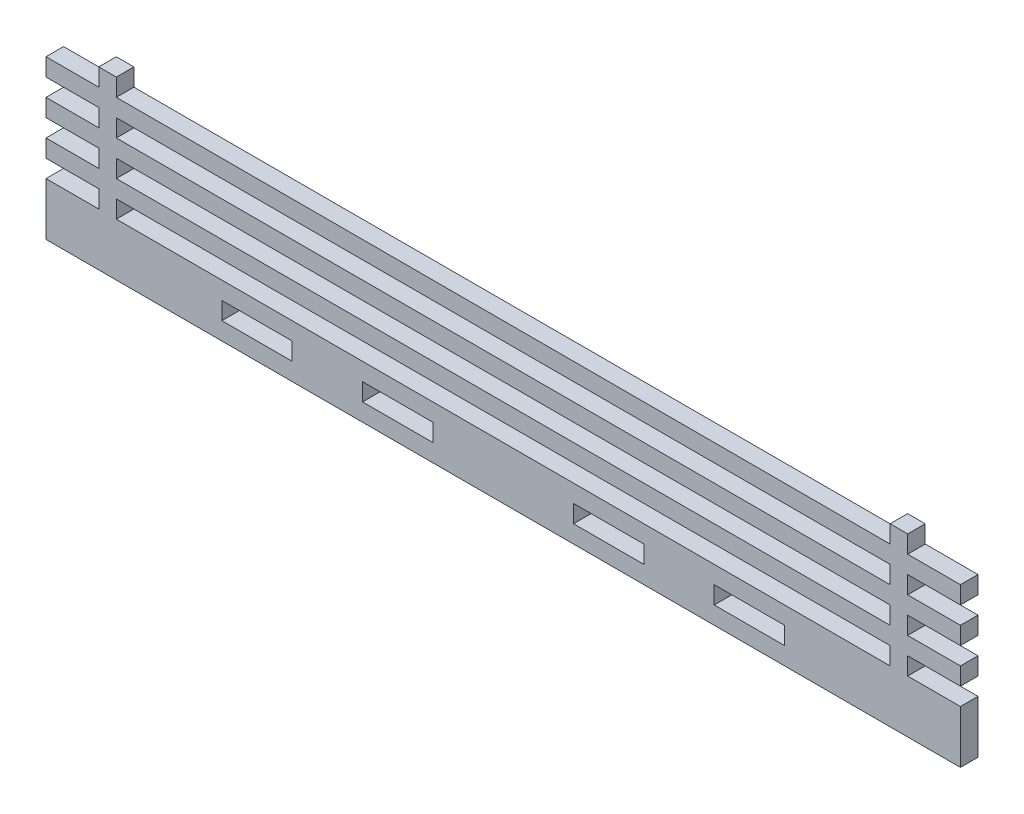
SolidWorks part; units mm, degrees
material "Beech"
ref_plane "Front" through (0, 0, 0) normal (0, 0, 1) x (1, 0, 0)
ref_plane "Top" through (0, 0, 0) normal (0, 1, 0) x (1, 0, 0)
ref_plane "Right" through (0, 0, 0) normal (1, 0, 0) x (0, 0, -1)
sketch "Sketch1" plane through (0, 0, 0) normal (0, 0, 1) x (1, 0, 0)
  line L0 (-65, 10) -> (65, 10) construction
  line L1 (-65, -12.5) -> (65, -12.5) construction
  line L2 (-65, -12.5) -> (-65, 12.5) construction
  line L3 (-65, 12.5) -> (65, 12.5) construction
  line L4 (65, -12.5) -> (65, 12.5) construction
  line L5 (-65, -12.5) -> (65, 12.5) construction
  line L6 (-65, 12.5) -> (65, -12.5) construction
  line L7 (-65, 7.5) -> (65, 7.5) construction
  line L8 (-65, 5) -> (65, 5) construction
  line L9 (-65, 2.5) -> (65, 2.5) construction
  line L10 (-65, 0) -> (65, 0) construction
  line L11 (-65, -2.5) -> (65, -2.5) construction
  line L12 (-65, -5) -> (65, -5) construction
  line L13 (-65, -7.5) -> (65, -7.5) construction
  line L14 (-65, -10) -> (65, -10) construction
  line L15 (-57.5, 12.5) -> (-57.5, -5) construction
  line L16 (0, 6.4448) -> (0, -3.7428) construction
  line L17 (57.5, 12.5) -> (57.5, -5) construction
  line L18 (-55, 12.5) -> (-55, -5) construction
  line L19 (55, 12.5) -> (55, -5) construction
  line L20 (-65, -12.5) -> (65, -12.5)
  line L21 (65, -12.5) -> (65, -5)
  line L22 (55, -5) -> (-55, -5)
  line L23 (57.5, -5) -> (57.5, -2.5)
  line L24 (57.5, -2.5) -> (65, -2.5)
  line L25 (65, -2.5) -> (65, 0)
  line L26 (65, 0) -> (57.5, 0)
  line L27 (57.5, 0) -> (57.5, 2.5)
  line L28 (57.5, 2.5) -> (65, 2.5)
  line L29 (65, 2.5) -> (65, 5)
  line L30 (65, 5) -> (57.5, 5)
  line L31 (57.5, 5) -> (57.5, 7.5)
  line L32 (57.5, 7.5) -> (65, 7.5)
  line L33 (65, 7.5) -> (65, 10)
  line L34 (65, 10) -> (57.5, 10)
  line L35 (57.5, 10) -> (57.5, 12.5)
  line L36 (57.5, 12.5) -> (55, 12.5)
  line L37 (55, 12.5) -> (55, 10)
  line L38 (55, 10) -> (-55, 10)
  line L39 (-55, 7.5) -> (55, 7.5)
  line L40 (55, 7.5) -> (55, 5)
  line L41 (55, 5) -> (-55, 5)
  line L42 (-55, 2.5) -> (55, 2.5)
  line L43 (55, 2.5) -> (55, 0)
  line L44 (55, 0) -> (-55, 0)
  line L45 (-55, -2.5) -> (55, -2.5)
  line L46 (55, -2.5) -> (55, -5)
  line L47 (57.5, -5) -> (65, -5)
  line L48 (-55, 7.5) -> (-55, 5)
  line L49 (-55, 2.5) -> (-55, 0)
  line L50 (-55, -2.5) -> (-55, -5)
  line L51 (-55, 12.5) -> (-55, 10)
  line L52 (-57.5, 12.5) -> (-55, 12.5)
  line L53 (-57.5, 10) -> (-57.5, 12.5)
  line L54 (-65, 10) -> (-57.5, 10)
  line L55 (-65, 7.5) -> (-65, 10)
  line L56 (-57.5, 7.5) -> (-65, 7.5)
  line L57 (-57.5, 5) -> (-57.5, 7.5)
  line L58 (-65, 5) -> (-57.5, 5)
  line L59 (-65, 2.5) -> (-65, 5)
  line L60 (-57.5, 2.5) -> (-65, 2.5)
  line L61 (-57.5, 0) -> (-57.5, 2.5)
  line L62 (-65, 0) -> (-57.5, 0)
  line L63 (-65, -2.5) -> (-65, 0)
  line L64 (-57.5, -2.5) -> (-65, -2.5)
  line L65 (-57.5, -5) -> (-57.5, -2.5)
  line L66 (-57.5, -5) -> (-65, -5)
  line L67 (-65, -12.5) -> (-65, -5)
  line L68 (-20, -10) -> (-20, -7.5)
  line L69 (-40, -10) -> (-30, -10)
  line L70 (-40, -10) -> (-40, -7.5)
  line L71 (-40, -7.5) -> (-30, -7.5)
  line L72 (-30, -10) -> (-30, -7.5)
  line L73 (-40, -10) -> (-30, -7.5) construction
  line L74 (-40, -7.5) -> (-30, -10) construction
  line L75 (-20, -10) -> (-10, -10)
  line L76 (-10, -10) -> (-10, -7.5)
  line L77 (-20, -7.5) -> (-10, -7.5)
  line L78 (20, -10) -> (10, -10)
  line L79 (10, -10) -> (10, -7.5)
  line L80 (20, -7.5) -> (10, -7.5)
  line L81 (20, -10) -> (20, -7.5)
  line L82 (40, -7.5) -> (30, -7.5)
  line L83 (30, -10) -> (30, -7.5)
  line L84 (40, -10) -> (30, -10)
  line L85 (40, -10) -> (40, -7.5)
  point P0 (0, 0)
  point P46 (0, -5)
  point P55 (0, 5)
  point P56 (0, 7.5)
  point P57 (0, 0)
  point P58 (0, 2.5)
  point P59 (0, -2.5)
  point P60 (0, 10)
  point P66 (0, -12.5)
  point P70 (-35, -8.75)
  dimension "D1" = 130
  dimension "D2" = 25
  dimension "D3" = 2.5
  dimension "D5" = 2.5
  dimension "D6" = 7.5
  dimension "D8" = 2.5
  dimension "D9" = 10
  dimension "D11" = 10
  dimension "D12" = 10
  dimension "D4" = 9
  dimension "D7" = 2
  dimension "D10" = 2
extrude "Boss-Extrude1" add sketch "Sketch1" along normal blind 2.5
